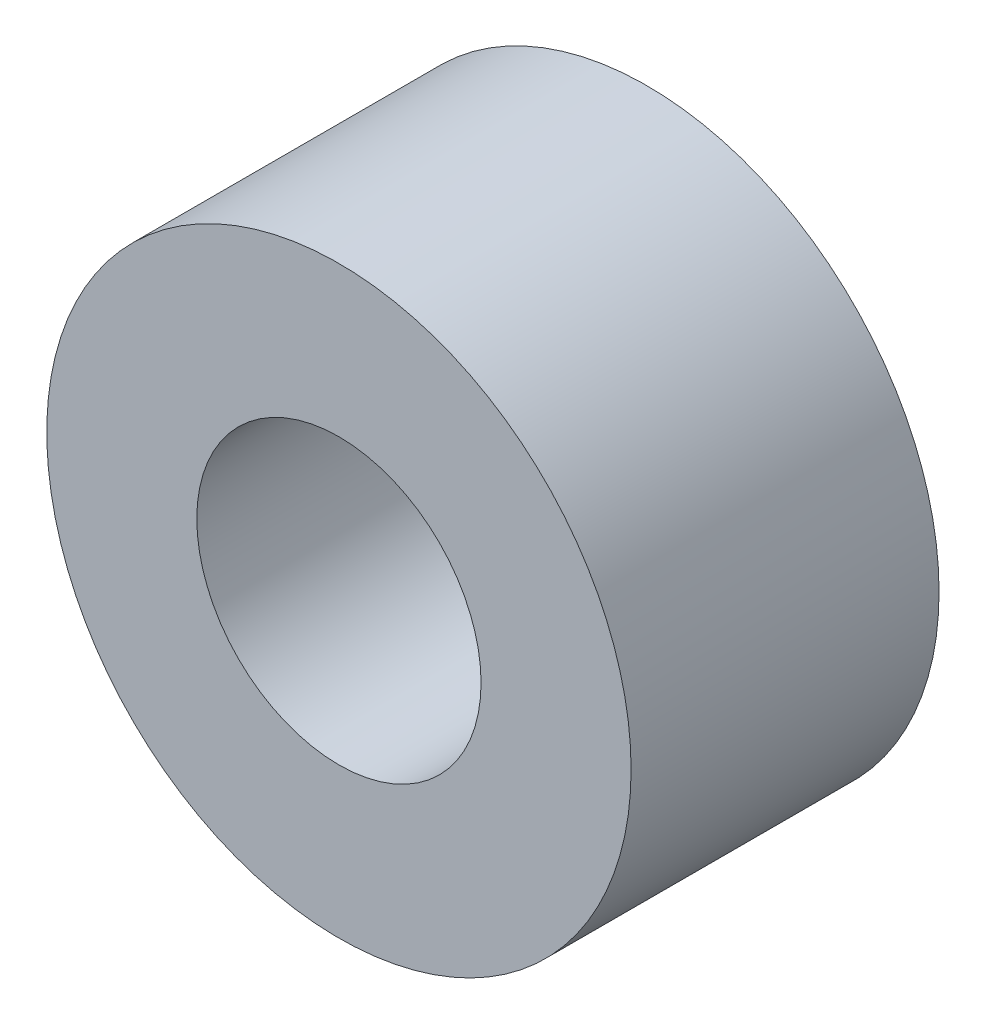
SolidWorks part; units mm, degrees
ref_plane "前视基准面" through (0, 0, 0) normal (0, 0, 1) x (1, 0, 0)
ref_plane "上视基准面" through (0, 0, 0) normal (0, 1, 0) x (1, 0, 0)
ref_plane "右视基准面" through (0, 0, 0) normal (1, 0, 0) x (0, 0, -1)
sketch "草图1" plane through (0, 0, 0) normal (0, 0, 1) x (1, 0, 0)
  circle A0 centre (0, 0) radius 18.5
  dimension "D1" = 37
extrude "拉伸1" add sketch "草图1" along normal blind 19.5
sketch "草图2" plane through (0, 0, 19.5) normal (0, 0, 1) x (1, 0, 0)
  circle A0 centre (0, 0) radius 9
extrude "切除-拉伸2" cut sketch "草图2" against normal blind 30
